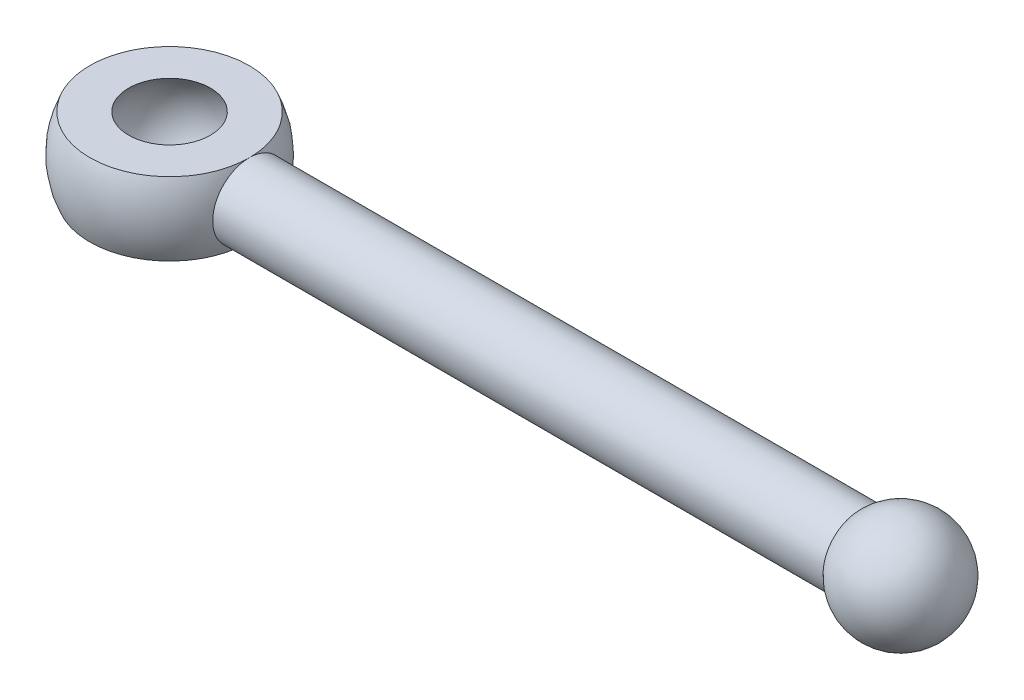
SolidWorks part; units mm, degrees
ref_plane "前视基准面" through (0, 0, 0) normal (0, 0, 1) x (1, 0, 0)
ref_plane "上视基准面" through (0, 0, 0) normal (0, 1, 0) x (1, 0, 0)
ref_plane "右视基准面" through (0, 0, 0) normal (1, 0, 0) x (0, 0, -1)
other "Configuration Table"
sketch "草图2" plane through (0, 0, 0) normal (0, 0, 1) x (1, 0, 0)
  line L0 (0, 0) -> (198.5542, 0) construction
  line L1 (0, 0) -> (0, 24.7734) construction
  line L2 (0, 10) -> (88.8197, 10)
  line L3 (100, 10) -> (100, -10) construction
  line L6 (0, 10) -> (-78.1826, 10)
  line L8 (0, 0) -> (-141.5281, 0) construction
  line L9 (-124, 0) -> (-115, 0)
  line L10 (-85, 0) -> (115, 0)
  arc A0 (115, 0) -> (88.8197, 10) centre (100, 0) ccw
  arc A1 (-78.1826, 10) -> (-124, 0) centre (-100, 0) ccw
  arc A2 (-85, 0) -> (-115, 0) centre (-100, 0) ccw
  point P15 (0, 10)
  dimension "D3" = 30
  dimension "D5" = 48
  dimension "D4" = 30
  dimension "D1" = 10
  dimension "D2" = 100
  dimension "D6" = 100
revolve "旋转1" add sketch "草图2" angle 360 about L0
sketch "草图3" plane through (0, 0, 0) normal (0, 0, 1) x (1, 0, 0)
  line L0 (0, 0) -> (-145.338, 0) construction
  line L1 (-140, 30) -> (-60, 30)
  line L2 (-140, 30) -> (-140, 10)
  line L3 (-140, 10) -> (-60, 10)
  line L4 (-60, 30) -> (-60, 10)
  line L5 (-60, -30) -> (-60, -10)
  line L6 (-140, -10) -> (-60, -10)
  line L7 (-140, -30) -> (-140, -10)
  line L8 (-140, -30) -> (-60, -30)
  dimension "D1" = 20
  dimension "D2" = 60
  dimension "D3" = 80
  dimension "D4" = 20
extrude "切除-拉伸2" cut sketch "草图3" against normal mid plane 138 contours L4 L3 L2 L1 | L5 L6 L7 L8
